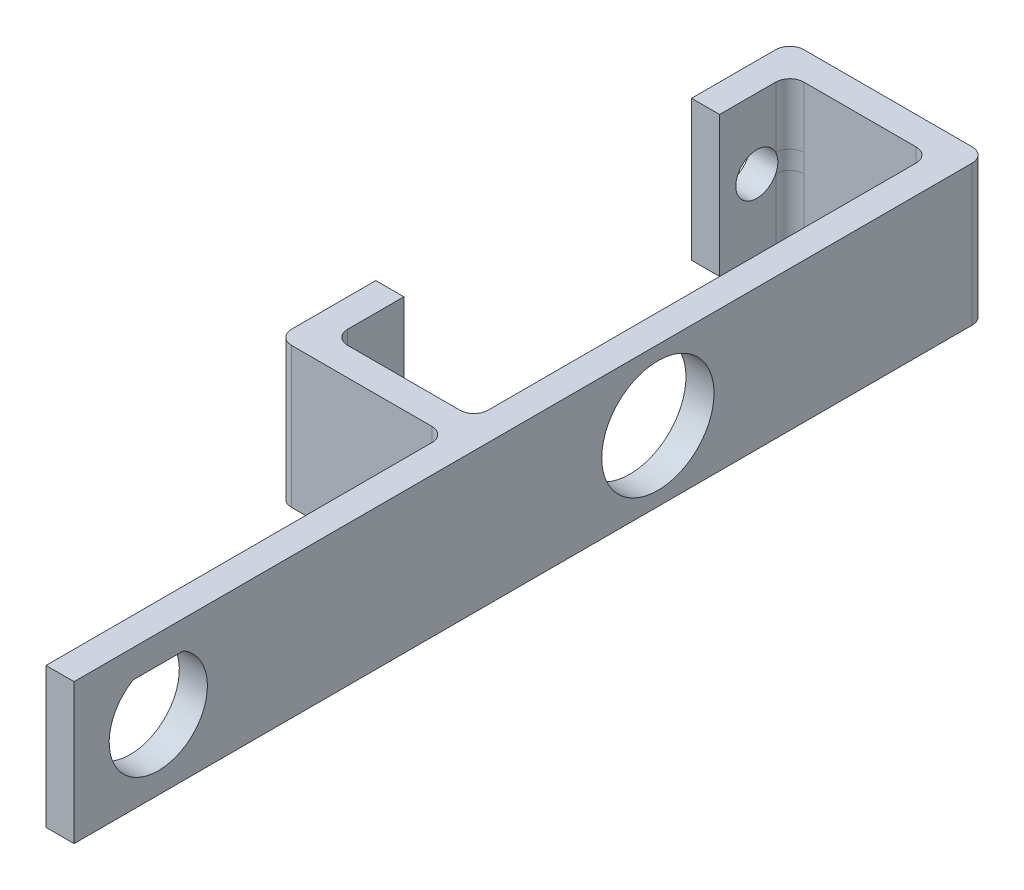
SolidWorks part; units mm, degrees
ref_plane "Front Plane" through (0, 0, 0) normal (0, 0, 1) x (1, 0, 0)
ref_plane "Top Plane" through (0, 0, 0) normal (0, 1, 0) x (1, 0, 0)
ref_plane "Right Plane" through (0, 0, 0) normal (1, 0, 0) x (0, 0, -1)
sketch "Sketch1" plane through (0, 0, 0) normal (0, 1, 0) x (1, 0, 0)
  line L0 (12, 5) -> (12, -27.5)
  line L7 (14, -58) -> (12, -58)
  line L13 (14, 7) -> (14, -58)
  line L14 (2, -22.5) -> (2, -27.5)
  line L20 (0, -22.5) -> (0, -29.5)
  line L23 (2, -27.5) -> (12, -27.5)
  line L26 (0, -29.5) -> (12, -29.5)
  line L28 (0, -22.5) -> (2, -22.5)
  line L29 (12, -29.5) -> (12, -58)
  line L37 (12, 5) -> (2, 5)
  line L40 (2, 5) -> (2, 0)
  line L41 (2, 0) -> (0, 0)
  line L43 (0, 7) -> (14, 7)
  line L44 (0, 7) -> (0, 0)
  dimension "D1" = 22.5
  dimension "D2" = 2
  dimension "D3" = 2
  dimension "D4" = 5
  dimension "D5" = 2
  dimension "D6" = 10
  dimension "D7" = 65
extrude "Boss-Extrude1" add sketch "Sketch1" along normal blind 10
sketch "Sketch2" plane through (0, 0, 0) normal (-1, 0, 0) x (0, 0, 1)
  line L0 (-2.65, 5) -> (0, 5) construction
  line L1 (0, 10) -> (0, 0) construction
  line L2 (25.15, 5) -> (22.5, 5) construction
  line L3 (22.5, 10) -> (22.5, 0) construction
  circle A0 centre (25.15, 5) radius 1.5
  circle A1 centre (-2.65, 5) radius 1.5
  dimension "D1" = 27.8
  dimension "D2" = 3
extrude "Cut-Extrude1" cut sketch "Sketch2" against normal up to surface (2 mm away) up to face at (2, 5, -2.5)
sketch "Sketch3" plane through (12, 0, 0) normal (-1, 0, 0) x (0, 0, 1)
  line L0 (25.15, 5) -> (16.4, 5) construction
  line L2 (50.1972, 8) -> (53.8028, 8)
  line L3 (58, 10) -> (58, 0) construction
  circle A0 centre (16.4, 5) radius 4
  circle A1 centre (25.15, 5) radius 1.5 construction
  circle A2 centre (25.15, 5) radius 1.5 construction
  arc A3 (50.1972, 8) -> (53.8028, 8) centre (52, 5) ccw
  dimension "D1" = 8
  dimension "D2" = 8.75
  dimension "D3" = 7
  dimension "D4" = 3
  dimension "D5" = 6
extrude "Cut-Extrude2" cut sketch "Sketch3" against normal up to surface (2 mm away) up to face at (14, 5, 25.5)
fillet "Fillet1" radius 1 8 edges at (14, 5, -7) (12, 5, 29.5) (12, 5, -5) (2, 5, -5) (2, 5, 27.5) (12, 5, 27.5) (0, 5, 29.5) (0, 5, -7)
